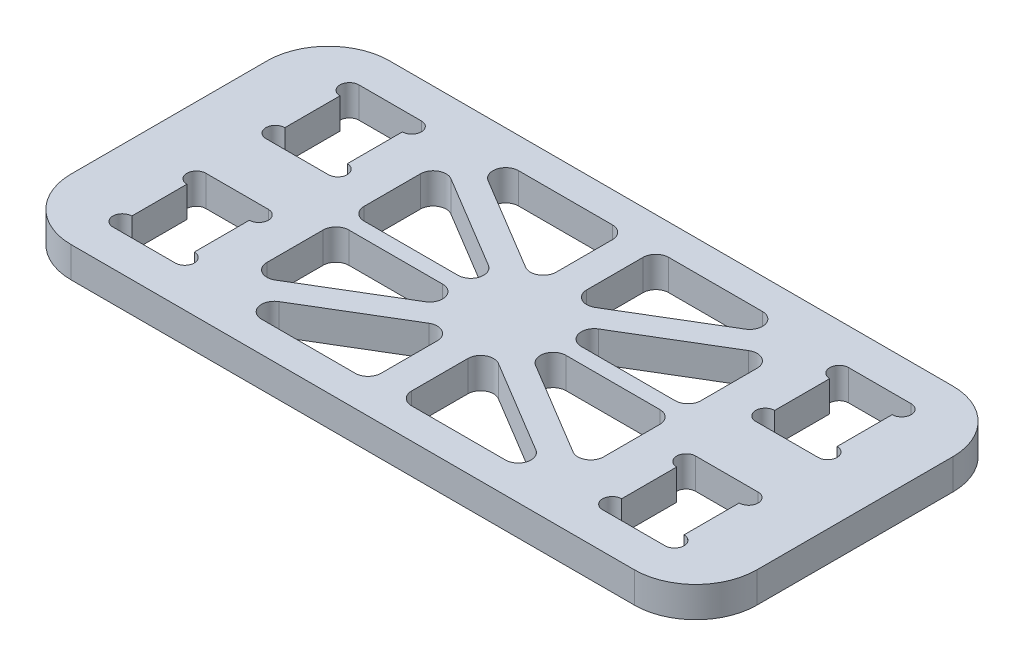
SolidWorks part; units mm, degrees
material "6061 合金"
ref_plane "前视基准面" through (0, 0, 0) normal (0, 0, 1) x (1, 0, 0)
ref_plane "上视基准面" through (0, 0, 0) normal (0, 1, 0) x (1, 0, 0)
ref_plane "右视基准面" through (0, 0, 0) normal (1, 0, 0) x (0, 0, -1)
other "Configuration Table"
sketch "草图1" plane through (0, 0, 0) normal (0, 1, 0) x (1, 0, 0)
  line L0 (0, 140.7121) -> (0, -152.4768) construction
  line L1 (-56, 26) -> (56, 26)
  line L2 (-56, 26) -> (-56, -26)
  line L3 (-56, -26) -> (56, -26)
  line L4 (56, 26) -> (56, -26)
  line L5 (-152.0124, 0) -> (209.2879, 0) construction
  line L6 (35, -5) -> (45, -5)
  line L7 (35, 20) -> (45, 20)
  line L8 (35, 20) -> (35, 5)
  line L9 (35, 5) -> (45, 5)
  line L10 (45, 20) -> (45, 5)
  line L15 (45, -20) -> (45, -5)
  line L16 (35, -20) -> (45, -20)
  line L17 (35, -20) -> (35, -5)
  line L18 (-35, -20) -> (-35, -5)
  line L19 (-35, -20) -> (-45, -20)
  line L20 (-45, -20) -> (-45, -5)
  line L21 (-35, -5) -> (-45, -5)
  line L22 (-35, 5) -> (-45, 5)
  line L23 (-45, 20) -> (-45, 5)
  line L24 (-35, 20) -> (-45, 20)
  line L25 (-35, 20) -> (-35, 5)
  dimension "D1" = 112
  dimension "D2" = 52
  dimension "D3" = 10
  dimension "D4" = 5
  dimension "D5" = 45
  dimension "D6" = 15
extrude "凸台-拉伸1" add sketch "草图1" along normal blind 5 contours L1 L4 L3 L2
other "移动面1" face at (-45, 2.5, -12.5) face at (-40, 2.5, -20) face at (-45, 2.5, 12.5) face at (-40, 2.5, 5) face at (-40, 2.5, 20) face at (-35, 2.5, 12.5) face at (-40, 2.5, -5) face at (-35, 2.5, -12.5) face at (40, 2.5, 20) face at (35, 2.5, 12.5) face at (45, 2.5, 12.5) face at (40, 2.5, 5) face at (40, 2.5, -5) face at (35, 2.5, -12.5) face at (40, 2.5, -20) face at (45, 2.5, -12.5) parameters "D1"=0.1
sketch "草图2" plane through (0, 5, 0) normal (0, 1, 0) x (1, 0, 0)
  line L0 (45.1, 4.9) -> (45.1, 20.1) construction
  line L1 (0, 0) -> (0, 45.2907) construction
  line L2 (40, 40.4409) -> (40, -36.2744) construction
  line L3 (45.1, -20.1) -> (45.1, -4.9) construction
  line L4 (34.9, -4.9) -> (34.9, -20.1) construction
  line L5 (45.1, 20.1) -> (34.9, 20.1) construction
  line L6 (34.9, 4.9) -> (45.1, 4.9) construction
  line L7 (45.1, -4.9) -> (34.9, -4.9) construction
  line L8 (34.9, -20.1) -> (45.1, -20.1) construction
  circle A0 centre (45.1, 18.55) radius 1.55
  circle A1 centre (45.1, 6.45) radius 1.55
  circle A2 centre (45.1, -6.45) radius 1.55
  circle A3 centre (45.1, -18.55) radius 1.55
  circle A4 centre (34.9, -18.55) radius 1.55
  circle A5 centre (34.9, -6.45) radius 1.55
  circle A6 centre (34.9, 6.45) radius 1.55
  circle A7 centre (34.9, 18.55) radius 1.55
  circle A8 centre (-34.9, 18.55) radius 1.55
  circle A9 centre (-34.9, 6.45) radius 1.55
  circle A10 centre (-34.9, -6.45) radius 1.55
  circle A11 centre (-34.9, -18.55) radius 1.55
  circle A12 centre (-45.1, -18.55) radius 1.55
  circle A13 centre (-45.1, -6.45) radius 1.55
  circle A14 centre (-45.1, 6.45) radius 1.55
  circle A15 centre (-45.1, 18.55) radius 1.55
  dimension "D1" = 3.1
extrude "切除-拉伸1" cut sketch "草图2" against normal blind 5
sketch "草图3" plane through (0, 5, 0) normal (0, 1, 0) x (1, 0, 0)
  line L0 (0, 0) -> (66.8883, 0) construction
  line L1 (0, 0) -> (0, 40.2589) construction
  line L2 (2.5, 21) -> (27.5, 21)
  line L3 (27.5, 21) -> (2.5, 6)
  line L4 (2.5, 6) -> (2.5, 21)
  line L5 (27.5, 16.25) -> (2.5, 1.25)
  line L6 (2.5, 1.25) -> (27.5, 1.25)
  line L7 (27.5, 1.25) -> (27.5, 16.25)
  line L8 (56, 26) -> (-56, 26) construction
  line L9 (-2.5, 1.25) -> (-27.5, 1.25)
  line L10 (-27.5, 16.25) -> (-2.5, 1.25)
  line L11 (-27.5, 1.25) -> (-27.5, 16.25)
  line L12 (-27.5, 21) -> (-2.5, 6)
  line L13 (-2.5, 21) -> (-27.5, 21)
  line L14 (-2.5, 6) -> (-2.5, 21)
  line L15 (2.5, -1.25) -> (27.5, -1.25)
  line L16 (27.5, -16.25) -> (2.5, -1.25)
  line L17 (27.5, -1.25) -> (27.5, -16.25)
  line L18 (27.5, -21) -> (2.5, -6)
  line L19 (2.5, -21) -> (27.5, -21)
  line L20 (2.5, -6) -> (2.5, -21)
  line L21 (-27.5, -1.25) -> (-27.5, -16.25)
  line L22 (-27.5, -16.25) -> (-2.5, -1.25)
  line L23 (-2.5, -1.25) -> (-27.5, -1.25)
  line L24 (-2.5, -21) -> (-27.5, -21)
  line L25 (-2.5, -6) -> (-2.5, -21)
  line L26 (-27.5, -21) -> (-2.5, -6)
  dimension "D1" = 2.5
  dimension "D2" = 25
  dimension "D3" = 15
  dimension "D4" = 2.5
  dimension "D7" = 5
extrude "切除-拉伸2" cut sketch "草图3" against normal blind 5
fillet "圆角1" radius 2.1 24 edges at (-27.5, 2.5, 1.25) (-27.5, 2.5, 16.25) (-2.5, 2.5, 1.25) (2.5, 2.5, 1.25) (27.5, 2.5, 16.25) (27.5, 2.5, 1.25) (27.5, 2.5, -1.25) (2.5, 2.5, -1.25) (27.5, 2.5, -16.25) (27.5, 2.5, -21) (2.5, 2.5, -6) (2.5, 2.5, -21) (-2.5, 2.5, -21) (-2.5, 2.5, -6) (-2.5, 2.5, -1.25) (-27.5, 2.5, -1.25) (-27.5, 2.5, -16.25) (-27.5, 2.5, -21) (27.5, 2.5, 21) (2.5, 2.5, 6) (2.5, 2.5, 21) (-2.5, 2.5, 21) (-2.5, 2.5, 6) (-27.5, 2.5, 21)
fillet "圆角2" radius 10 4 edges at (-56, 2.5, 26) (-56, 2.5, -26) (56, 2.5, -26) (56, 2.5, 26)
